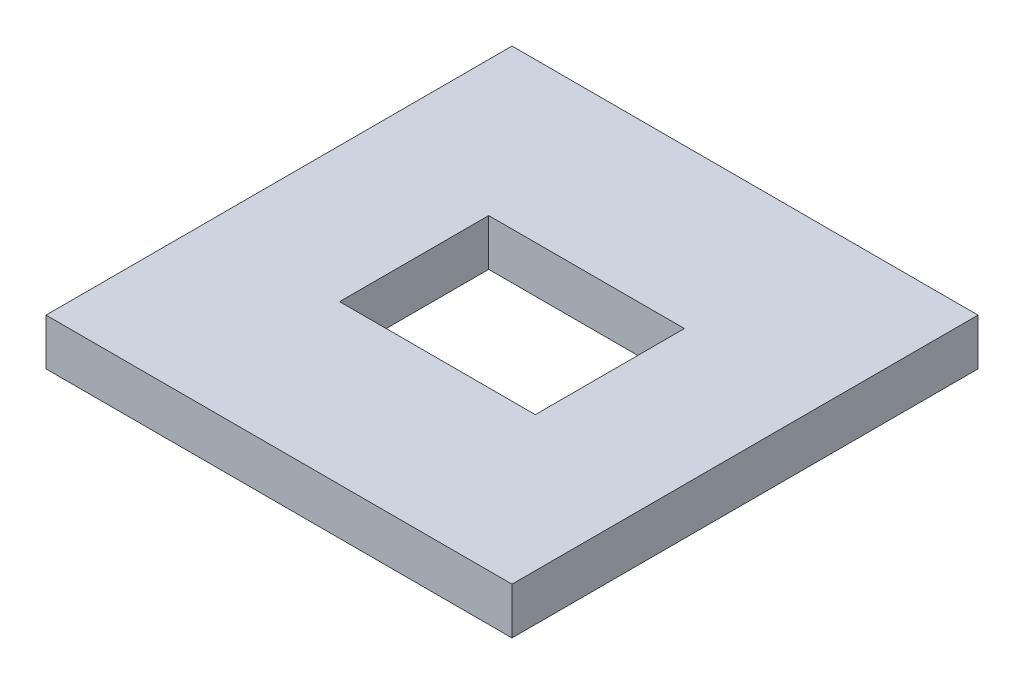
SolidWorks part; units mm, degrees
ref_plane "Front Plane" through (0, 0, 0) normal (0, 0, 1) x (1, 0, 0)
ref_plane "Top Plane" through (0, 0, 0) normal (0, 1, 0) x (1, 0, 0)
ref_plane "Right Plane" through (0, 0, 0) normal (1, 0, 0) x (0, 0, -1)
sketch "Sketch1" plane through (0, 0, 0) normal (0, 1, 0) x (1, 0, 0)
  line L1 (-25, -25) -> (25, -25)
  line L2 (-25, -25) -> (-25, 25)
  line L3 (-25, 25) -> (25, 25)
  line L4 (25, -25) -> (25, 25)
  line L5 (-25, -25) -> (25, 25) construction
  line L6 (-25, 25) -> (25, -25) construction
  line L7 (-10.5, -8) -> (10.5, -8)
  line L8 (-10.5, -8) -> (-10.5, 8)
  line L9 (-10.5, 8) -> (10.5, 8)
  line L10 (10.5, -8) -> (10.5, 8)
  line L11 (-10.5, -8) -> (10.5, 8) construction
  line L12 (-10.5, 8) -> (10.5, -8) construction
  point P0 (0, 0)
  point P6 (0, 0)
  dimension "D1" = 50
  dimension "D2" = 50
  dimension "D3" = 21
  dimension "D4" = 16
extrude "Boss-Extrude1" add sketch "Sketch1" along normal blind 5
